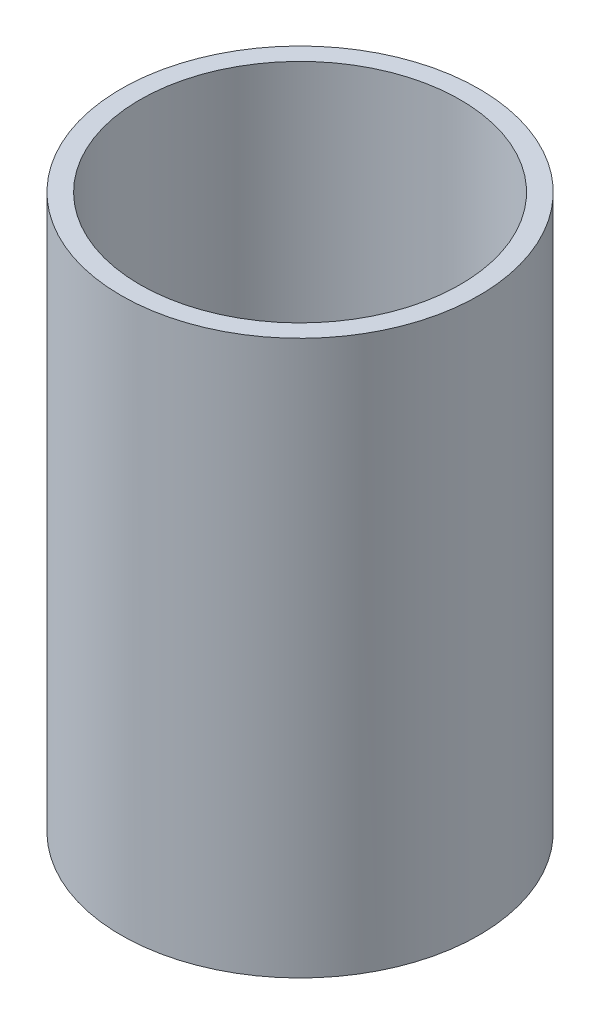
SolidWorks part; units mm, degrees
ref_plane "Front Plane" through (0, 0, 0) normal (0, 0, 1) x (1, 0, 0)
ref_plane "Top Plane" through (0, 0, 0) normal (0, 1, 0) x (1, 0, 0)
ref_plane "Right Plane" through (0, 0, 0) normal (1, 0, 0) x (0, 0, -1)
sketch "Sketch1" plane through (0, 0, 0) normal (0, 1, 0) x (1, 0, 0)
  circle A0 centre (0, 0) radius 19
  circle A1 centre (0, 0) radius 17
  dimension "D1" = 38
  dimension "D2" = 2
extrude "Boss-Extrude1" add sketch "Sketch1" along normal blind 58.8
sketch "Sketch2" plane through (0, 0, 0) normal (0, 0, 1) x (1, 0, 0)
  circle A1 centre (0, 0) radius 10.45
  dimension "D2" = 20.9
extrude "Cut-Extrude1" cut sketch "Sketch2" against normal through all
